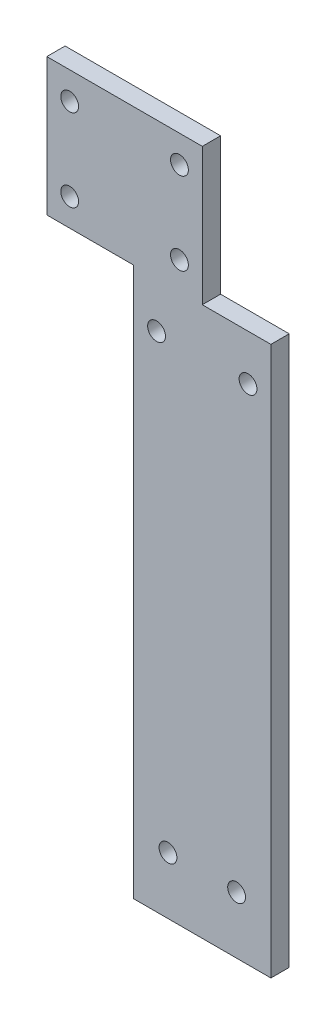
SolidWorks part; units mm, degrees
ref_plane "前视基准面" through (0, 0, 0) normal (0, 0, 1) x (1, 0, 0)
ref_plane "上视基准面" through (0, 0, 0) normal (0, 1, 0) x (1, 0, 0)
ref_plane "右视基准面" through (0, 0, 0) normal (1, 0, 0) x (0, 0, -1)
sketch "草图1" plane through (0, 0, 0) normal (0, 0, 1) x (1, 0, 0)
  line L0 (0, 0) -> (30, 0)
  line L1 (30, 0) -> (30, 99.9277)
  line L2 (15, 150) -> (-19, 150)
  line L3 (0, 100) -> (0, 0)
  line L5 (15, 120) -> (15, 150)
  line L7 (-19, 120) -> (-19, 150)
  line L8 (15, 120) -> (30, 120)
  line L9 (-19, 120) -> (0, 120)
  line L12 (0, 120) -> (0, 100)
  line L13 (30, 120) -> (30, 99.9277)
  circle A0 centre (7.5, 12.5) radius 1.95
  circle A1 centre (22.5, 12.5) radius 1.95
  circle A2 centre (-14, 144) radius 1.95
  circle A3 centre (10, 144) radius 1.95
  circle A4 centre (-14, 126) radius 1.95
  circle A5 centre (10, 126) radius 1.95
  circle A6 centre (5, 110) radius 1.95
  circle A7 centre (25, 110) radius 1.95
  point P18 (25.7936, 110.763)
  point P21 (16.5505, 104.9973)
  point P23 (0, 0)
  point P24 (-0.7539, 100)
  point P25 (6.3295, 110)
  point P26 (30.4832, 100)
  point P28 (0, 0)
  point P34 (-15.9125, 150)
  point P35 (31.0696, 111.6941)
  point P36 (27.4662, 105.77)
  point P37 (37.6868, 150)
  point P38 (38.5239, 150)
  dimension "D6" = 3.9
  dimension "D11" = 3.9
  dimension "D1" = 30
  dimension "D2" = 5
  dimension "D3" = 15
  dimension "D4" = 7.5
  dimension "D5" = 12.5
  dimension "D7" = 24
  dimension "D8" = 5
  dimension "D9" = 6
  dimension "D10" = 18
  dimension "D12" = 30
  dimension "D13" = 5
  dimension "D14" = 150
  dimension "D15" = 5
  dimension "D16" = 10
  dimension "D17" = 15
extrude "凸台-拉伸1" add sketch "草图1" along normal blind 4
